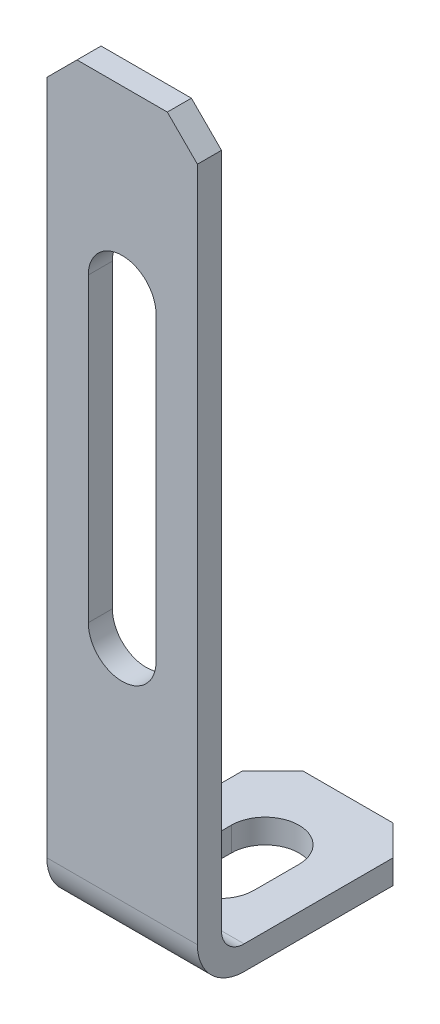
SolidWorks part; units mm, degrees
ref_plane "Front Plane" through (0, 0, 0) normal (0, 0, 1) x (1, 0, 0)
ref_plane "Top Plane" through (0, 0, 0) normal (0, 1, 0) x (1, 0, 0)
ref_plane "Right Plane" through (0, 0, 0) normal (1, 0, 0) x (0, 0, -1)
ref_plane "Plane1" through (10, 0, 0) normal (1, 0, 0) x (0, 0, -1)
sketch "Sketch1" plane through (10, 0, 0) normal (1, 0, 0) x (0, 0, -1)
  line L0 (0, 50) -> (0, 0)
  line L1 (0, 0) -> (15, 0)
  line L2 (15, 0) -> (15, 50)
  line L3 (15, 50) -> (0, 50)
extrude "Boss-Extrude1" add sketch "Sketch1" against normal blind 10
sketch "Sketch2" plane through (0, 0, 0) normal (-1, 0, 0) x (0, 0, 1)
  line L0 (-15, 1.6) -> (-1.6, 1.6)
  line L1 (-1.6, 1.6) -> (-1.6, 50)
  line L2 (-1.6, 50) -> (-15, 50)
  line L3 (-15, 50) -> (-15, 1.6)
extrude "Cut-Extrude1" cut sketch "Sketch2" against normal through all
sketch "Sketch3" plane through (0, 1.6, 0) normal (0, 1, 0) x (-1, 0, 0)
  line L0 (-2.75, -9.5) -> (-2.75, -6.5)
  line L1 (-7.25, -6.5) -> (-7.25, -9.5)
  arc A0 (-7.25, -9.5) -> (-2.75, -9.5) centre (-5, -9.5) ccw
  arc A1 (-2.75, -6.5) -> (-7.25, -6.5) centre (-5, -6.5) ccw
extrude "Cut-Extrude2" cut sketch "Sketch3" against normal through all
sketch "Sketch4" plane through (0, 0, 0) normal (0, 0, 1) x (1, 0, 0)
  line L0 (7.25, 18) -> (7.25, 38)
  line L1 (2.75, 38) -> (2.75, 18)
  arc A0 (2.75, 18) -> (7.25, 18) centre (5, 18) ccw
  arc A1 (7.25, 38) -> (2.75, 38) centre (5, 38) ccw
extrude "Cut-Extrude3" cut sketch "Sketch4" against normal through all
chamfer "Chamfer1" distance 2 angle 45 4 edges at (0, 50, -0.8) (0, 0.8, -15) (10, 0.8, -15) (10, 50, -0.8)
fillet "Fillet1" radius 1.5 1 edges at (5, 1.6, -1.6)
fillet "Fillet2" radius 3.1 1 edges at (5, 0, 0)
